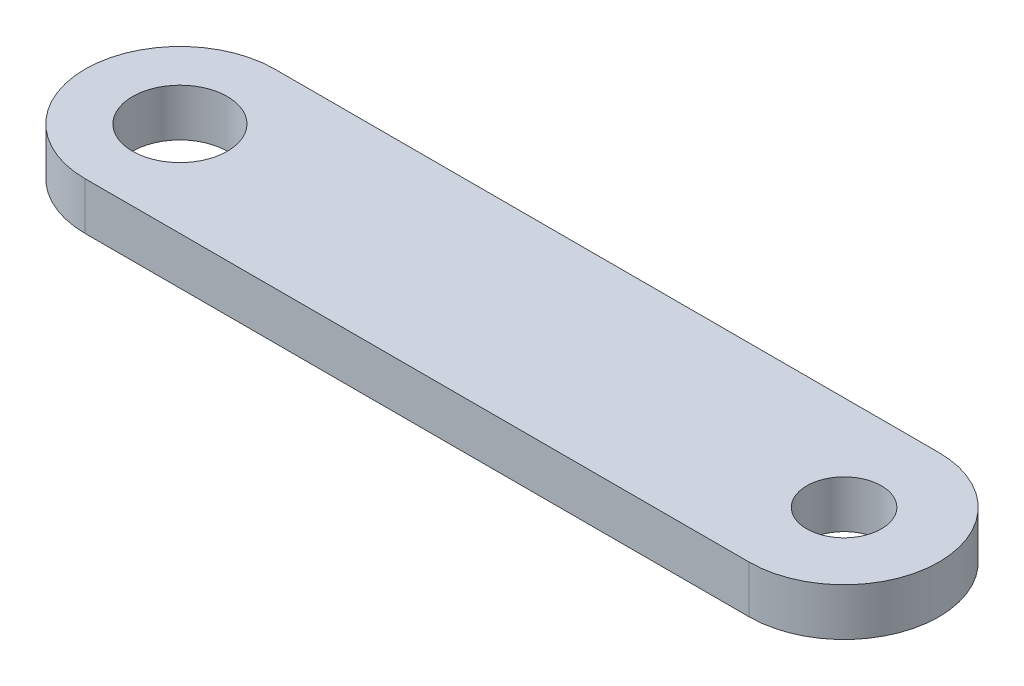
SolidWorks part; units mm, degrees
ref_plane "Front Plane" through (0, 0, 0) normal (0, 0, 1) x (1, 0, 0)
ref_plane "Top Plane" through (0, 0, 0) normal (0, 1, 0) x (1, 0, 0)
ref_plane "Right Plane" through (0, 0, 0) normal (1, 0, 0) x (0, 0, -1)
sketch "Sketch1" plane through (0, 0, 0) normal (0, 1, 0) x (1, 0, 0)
  line L0 (0, 0) -> (44.45, 0) construction
  line L1 (0, 6.35) -> (44.45, 6.35)
  line L2 (0, -6.35) -> (44.45, -6.35)
  arc A0 (0, 6.35) -> (0, -6.35) centre (0, 0) ccw
  arc A1 (44.45, -6.35) -> (44.45, 6.35) centre (44.45, 0) ccw
  circle A2 centre (0, 0) radius 3.175
  circle A3 centre (44.45, 0) radius 2.5
  point P3 (22.225, 0)
  dimension "D2" = 6.35
  dimension "D3" = 6.35
  dimension "D4" = 5
  dimension "D1" = 44.45
extrude "Boss-Extrude1" add sketch "Sketch1" along normal blind 3.175
